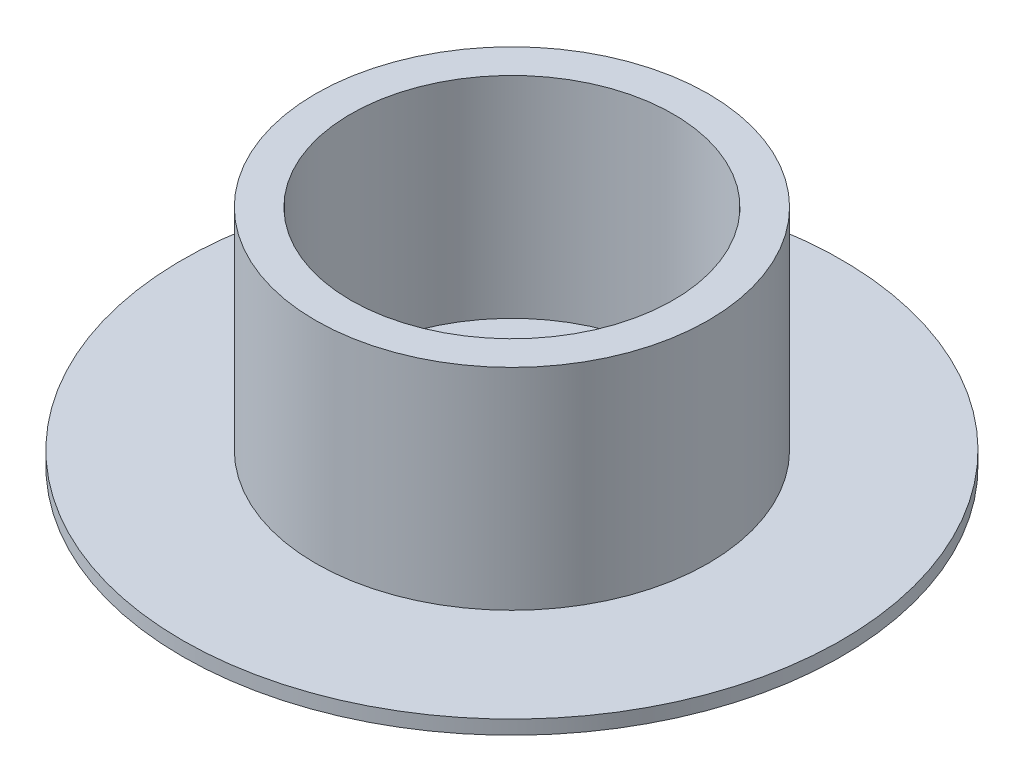
SolidWorks part; units mm, degrees
ref_plane "Спереди" through (0, 0, 0) normal (0, 0, 1) x (1, 0, 0)
ref_plane "Сверху" through (0, 0, 0) normal (0, 1, 0) x (1, 0, 0)
ref_plane "Справа" through (0, 0, 0) normal (1, 0, 0) x (0, 0, -1)
sketch "Эскиз1" plane through (0, 0, 0) normal (0, 1, 0) x (1, 0, 0)
  circle A0 centre (0, 0) radius 47
  dimension "D1" = 94
extrude "Бобышка-Вытянуть1" add sketch "Эскиз1" along normal blind 2
ref_plane "Плоскость4" through (0, 2, 0) normal (0, 1, 0) x (1, 0, 0)
sketch "Эскиз4" plane through (0, 2, 0) normal (0, 1, 0) x (1, 0, 0)
  circle A0 centre (0, 0) radius 23
  circle A1 centre (0, 0) radius 28
  dimension "D1" = 46
extrude "Бобышка-Вытянуть2" add sketch "Эскиз4" along normal blind 30
